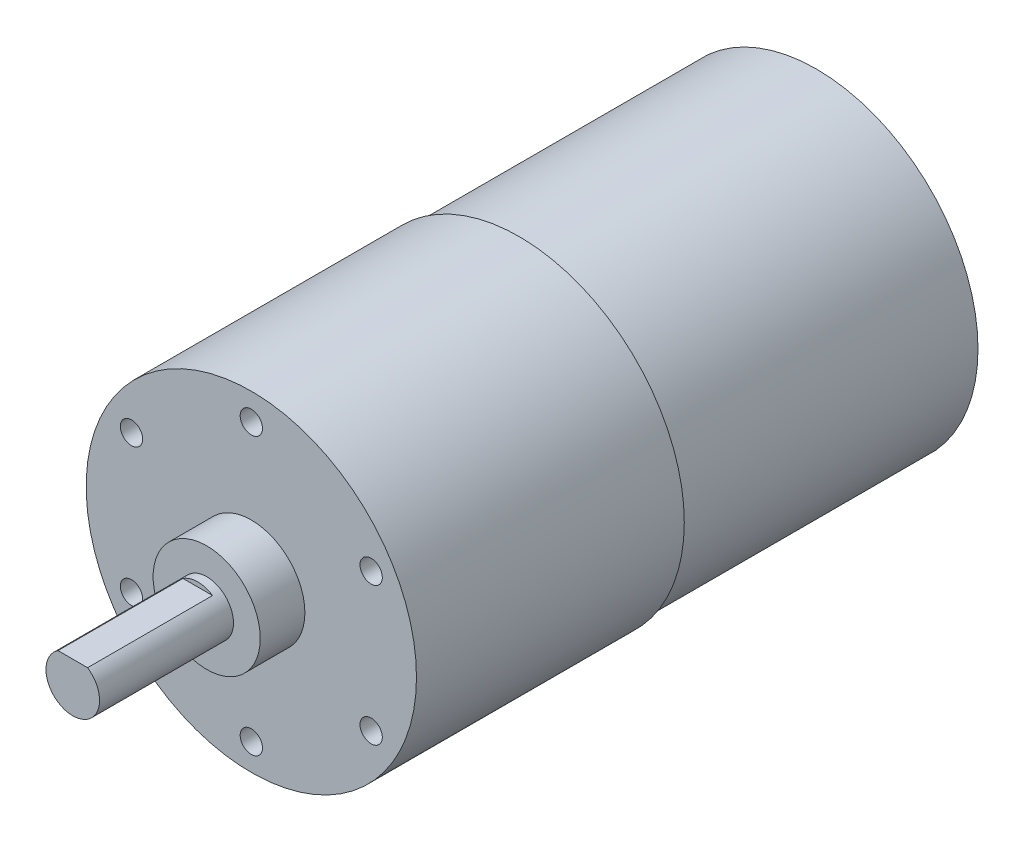
SolidWorks part; units mm, degrees
ref_plane "Front Plane" through (0, 0, 0) normal (0, 0, 1) x (1, 0, 0)
ref_plane "Top Plane" through (0, 0, 0) normal (0, 1, 0) x (1, 0, 0)
ref_plane "Right Plane" through (0, 0, 0) normal (1, 0, 0) x (0, 0, -1)
sketch "Sketch1" plane through (0, 0, 0) normal (0, 0, 1) x (1, 0, 0)
  circle A0 centre (0, 0) radius 18.5
  dimension "D1" = 37
extrude "Boss-Extrude1" add sketch "Sketch1" along normal blind 30
sketch "Sketch2" plane through (0, 0, 0) normal (0, 0, -1) x (-1, 0, 0)
  circle A0 centre (0, 0) radius 18.1
  dimension "D1" = 36.2
extrude "Boss-Extrude2" add sketch "Sketch2" along normal blind 33.3
sketch "Sketch3" plane through (0, 0, 30) normal (0, 0, 1) x (1, 0, 0)
  circle A0 centre (0, 0) radius 6
  dimension "D1" = 12
extrude "Boss-Extrude3" add sketch "Sketch3" along normal blind 5
sketch "Sketch4" plane through (0, 0, 35) normal (0, 0, 1) x (1, 0, 0)
  circle A0 centre (0, 0) radius 3
  dimension "D1" = 6
extrude "Boss-Extrude4" add sketch "Sketch4" along normal blind 1
sketch "Sketch5" plane through (0, 0, 36) normal (0, 0, 1) x (1, 0, 0)
  line L1 (-1.6583, 2.5) -> (1.6583, 2.5)
  arc A0 (-1.6583, 2.5) -> (1.6583, 2.5) centre (0, 0) ccw
  circle A1 centre (0, 0) radius 3 construction
  point P5 (0, 2.5)
  point P6 (0, -3)
  dimension "D1" = 5.5
extrude "Boss-Extrude5" add sketch "Sketch5" along normal blind 14
sketch "Sketch10" plane through (0, 0, 30) normal (0, 0, 1) x (1, 0, 0)
  point P0 (0, 0)
hole_wizard "M3x0.5 Tapped Hole1" positions "Sketch11" profile "Sketch12" tap size "M3x0.5" standard "ANSI Metric"
sketch "Sketch11" plane through (0, 0, 30) normal (0, 0, 1) x (1, 0, 0)
  line L0 (0, 0) -> (0, 15.5) construction
  point P0 (0, 15.5)
  point P8 (13.4234, 7.75)
  point P9 (13.4234, -7.75)
  point P10 (0, -15.5)
  point P11 (-13.4234, -7.75)
  point P12 (-13.4234, 7.75)
  dimension "D3" = 15.5
  dimension "D2" = 6
sketch "Sketch12" plane through (0, 15.5, 30) normal (1, 0, 0) x (0, -1, 0)
  line L0 (0, 0) -> (0, 6.7511)
  line L1 (0, 6.7511) -> (1.25, 6)
  line L2 (1.25, 6) -> (1.25, 0)
  line L5 (1.25, 0) -> (0, 0)
  line L10 (0, 6.7511) -> (-1.25, 6) construction
  line L11 (0, -6.35) -> (0, 107.95) construction
  dimension "Tap Drill Dia." = 2.5
  dimension "Tap Drill Depth" = 6
  dimension "Drill Angle" = 118
cosmetic thread "Hole Thread8" parameters "D1"=6, "D2"=3
cosmetic thread "Hole Thread9" parameters "D1"=6, "D2"=3
cosmetic thread "Hole Thread10" parameters "D1"=6, "D2"=3
cosmetic thread "Hole Thread11" parameters "D1"=6, "D2"=3
cosmetic thread "Hole Thread12" parameters "D1"=6, "D2"=3
cosmetic thread "Hole Thread13" parameters "D1"=6, "D2"=3
equation "\"PCB Width\"= 1940mil"
equation "\"PCB Height\"= 2210mil"
equation "\"PCB Thickness\"= 63mil"
equation "\"Motor Body Front Diameter\"= 37mm"
equation "\"Motor Body Front Length\"= 30mm"
equation "\"Motor Bearing Length\"= 5mm"
equation "\"Motor Body Back Length\"= 33.3mm"
equation "\"Motor PCR\"= 31mm / 2"
equation "\"Large PVC Fittings Wall Thickness\"= 15in / 64"
equation "\"Large PVC Pipe Outer Diameter\"= 3.5in"
equation "\"Box Width\"= 2 * \"Motor Bearing Length\" + \"Motor Body Front Length\" + \"Motor Body Back Length\" + 0.5in"
equation "\"Box Hole Center to Edge Distance\"= 250mil"
equation "\"Box Ceiling and Floor Thickness\"= 2 * \"Box Hole Center to Edge Distance\""
equation "\"Box Height\"= 2 * \"Box Ceiling and Floor Thickness\" + \"PCB Height\" + 0.5in"
equation "\"Box Back Depth\"= \"Large PVC Fittings Wall Thickness\" + \"Large PVC Pipe Outer Diameter\" / 2 + \"Motor Body Front Diameter\" / 2"
equation "\"D1@Sketch1\"=\"Motor Body Front Diameter\""
equation "\"D1@Boss-Extrude1\"=\"Motor Body Front Length\""
equation "\"D1@Boss-Extrude2\"=\"Motor Body Back Length\""
equation "\"D1@Boss-Extrude3\"=\"Motor Bearing Length\""
equation "\"D3@Sketch11\"=\"Motor PCR\""
